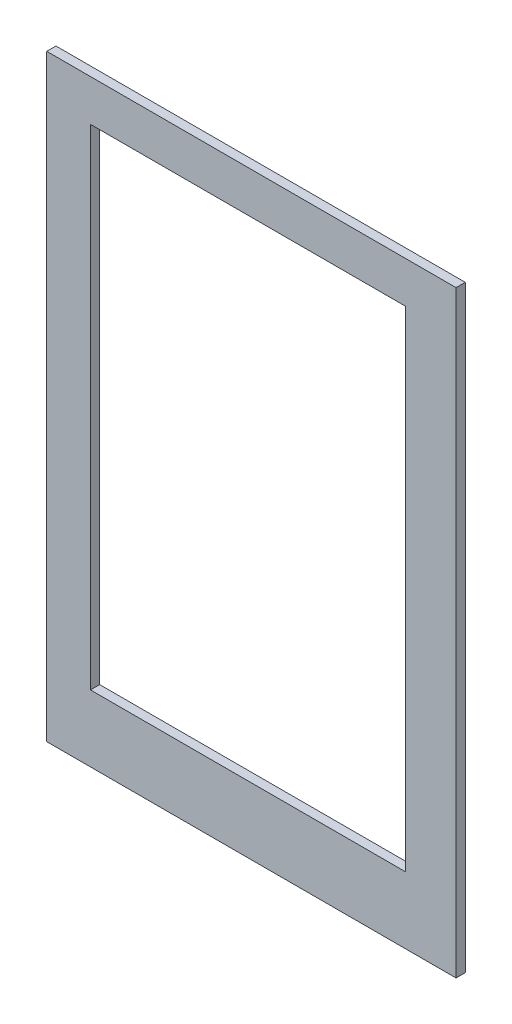
SolidWorks part; units mm, degrees
ref_plane "Front Plane" through (0, 0, 0) normal (1, 0, 0) x (0, 1, 0)
ref_plane "Top Plane" through (0, 0, 0) normal (0, 0, 1) x (0, 1, 0)
ref_plane "Right Plane" through (0, 0, 0) normal (0, 1, 0) x (-1, 0, 0)
sketch "Sketch1" plane through (0, 0, -68.6737) normal (0, 0, 1) x (1, 0, 0)
  line L0 (14.5651, 109.1247) -> (-143.4349, 109.1247) construction
  line L1 (-134.4349, 101.1247) -> (2.5651, 101.1247)
  line L2 (-134.4349, 101.1247) -> (-134.4349, -111.8753)
  line L3 (-134.4349, -111.8753) -> (2.5651, -111.8753)
  line L4 (2.5651, 101.1247) -> (2.5651, -111.8753)
  line L5 (-153.4349, 119.1247) -> (24.5651, 119.1247)
  line L6 (-153.4349, 119.1247) -> (-153.4349, -140.8753)
  line L7 (-153.4349, -140.8753) -> (24.5651, -140.8753)
  line L8 (24.5651, 119.1247) -> (24.5651, -140.8753)
  line L9 (-143.4349, 109.1247) -> (-143.4349, -130.8753) construction
  line L10 (-143.4349, -130.8753) -> (14.5651, -130.8753) construction
  line L11 (14.5651, -130.8753) -> (14.5651, 109.1247) construction
  dimension "D1" = 10
  dimension "D2" = 10
  dimension "D3" = 10
  dimension "D4" = 10
extrude "Boss-Extrude1" add sketch "Sketch1" along normal blind 4
